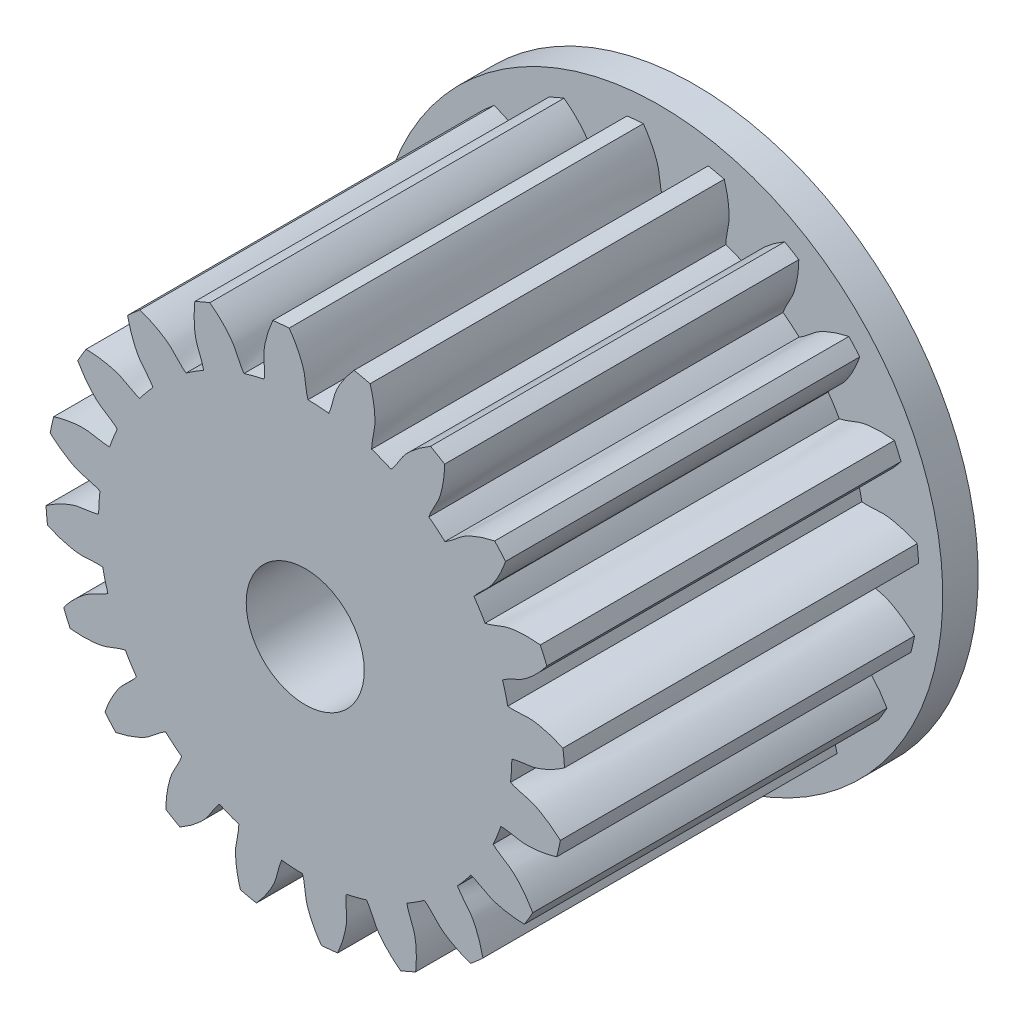
SolidWorks part; units mm, degrees
ref_plane "前视基准面" through (0, 0, 0) normal (0, 0, 1) x (1, 0, 0)
ref_plane "上视基准面" through (0, 0, 0) normal (0, 1, 0) x (1, 0, 0)
ref_plane "右视基准面" through (0, 0, 0) normal (1, 0, 0) x (0, 0, -1)
sketch "草图1" plane through (0, 0, 0) normal (0, 0, 1) x (1, 0, 0)
  circle A0 centre (0, 0) radius 8.75
  circle A1 centre (0, 0) radius 2.5
extrude "凸台-拉伸1" add sketch "草图1" along normal blind 15
sketch "草图2" plane through (0, 0, 0) normal (0, 0, 1) x (1, 0, 0)
  arc A0 (10.9141, 1.3717) -> (10.979, 0.68) centre (0, 0) cw
  arc A1 (8.5755, 1.7386) -> (8.7492, -0.115) centre (0, 0) cw
  spline S0 degree 3 poles (10.979, 0.68) (10.7796, 0.5417) (10.4722, 0.3535) (10.0421, 0.161) (9.5159, -0.0262) (9.0613, -0.0125) (8.7492, -0.115) knots 0 0 0 0 0.304015 0.449161 0.589717 1 1 1 1
  spline S1 degree 3 poles (10.9141, 1.3717) (10.6926, 1.4706) (10.3556, 1.5984) (9.8972, 1.7077) (9.3453, 1.7939) (8.9012, 1.6959) (8.5755, 1.7386) knots 0 0 0 0 0.304015 0.449161 0.589717 1 1 1 1
extrude "凸台-拉伸2" add sketch "草图2" along normal blind 15
pattern_circular "阵列(圆周)1" count 20 over 360 about axis through (0, 0, 15) along (0, 0, -1) of "凸台-拉伸2"
sketch "草图4" plane through (0, 0, 0) normal (0, 0, -1) x (-1, 0, 0)
  circle A0 centre (0, 0) radius 7
  circle A1 centre (0, 0) radius 12
  dimension "D1" = 14
  dimension "D2" = 24
extrude "凸台-拉伸4" add sketch "草图4" along normal blind 1.5
sketch "草图6" plane through (0, 0, 0) normal (0, 0, -1) x (-1, 0, 0)
  circle A1 centre (0, 0) radius 7
  circle A2 centre (0, 0) radius 7
  dimension "D1" = 0
extrude "切除-拉伸1" cut sketch "草图6" against normal blind 0.5
ref_plane "基准面1" through (-5.3054, -9.636, 0) normal (0, 0, -1) x (-1, 0, 0)
